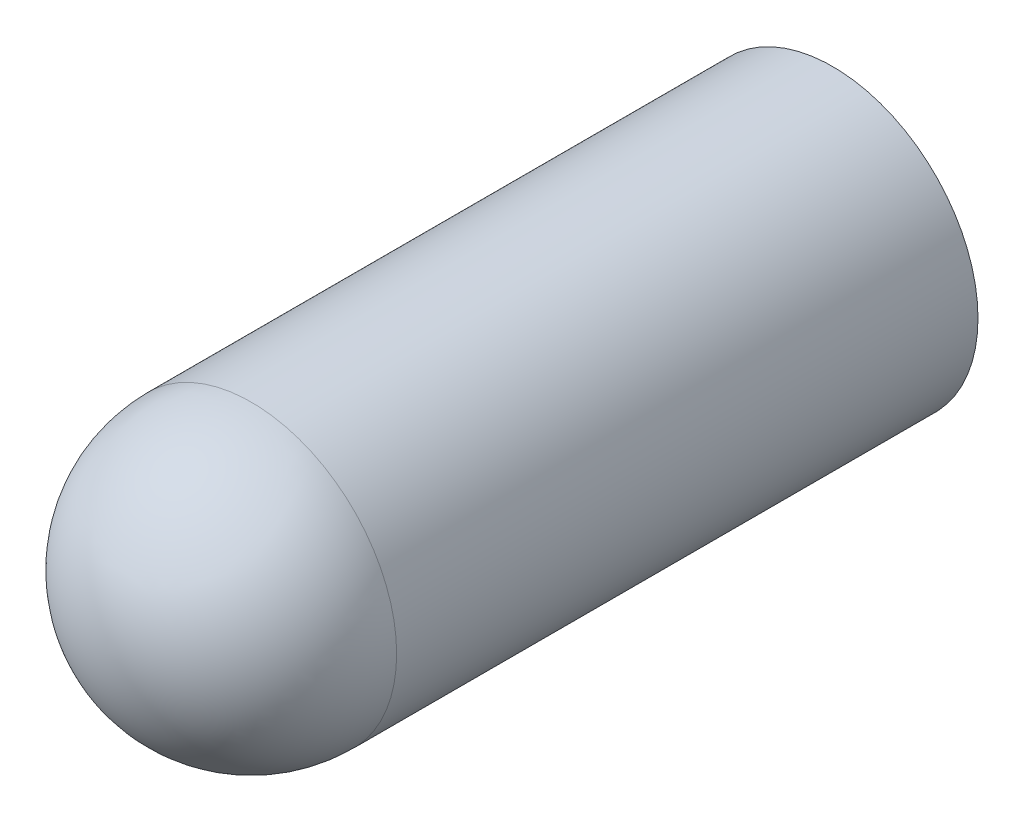
SolidWorks part; units mm, degrees
ref_plane "前视基准面" through (0, 0, 0) normal (0, 0, 1) x (1, 0, 0)
ref_plane "上视基准面" through (0, 0, 0) normal (0, 1, 0) x (1, 0, 0)
ref_plane "右视基准面" through (0, 0, 0) normal (1, 0, 0) x (0, 0, -1)
sketch "草图1" plane through (0, 0, 0) normal (0, 0, 1) x (1, 0, 0)
  circle A0 centre (0, 0) radius 1
  dimension "D1" = 2
extrude "凸台-拉伸1" add sketch "草图1" along normal blind 5
fillet "圆角1" radius 1 1 edges at (1, 0, 5)
